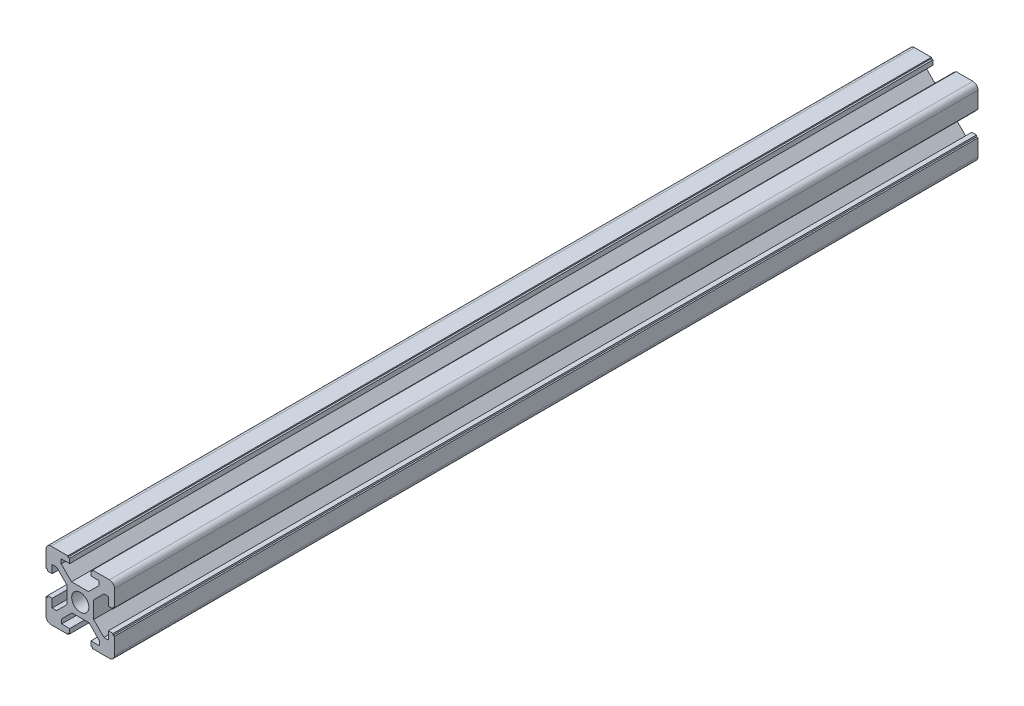
SolidWorks part; units mm, degrees
ref_plane "Front Plane" through (0, 0, 0) normal (0, 0, 1) x (1, 0, 0)
ref_plane "Top Plane" through (0, 0, 0) normal (0, 1, 0) x (1, 0, 0)
ref_plane "Right Plane" through (0, 0, 0) normal (1, 0, 0) x (0, 0, -1)
ref_plane "Plane1" through (0, 0, 0) normal (0, 0, -1) x (-1, 0, 0)
sketch "Sketch1" plane through (0, 0, 0) normal (0, 0, -1) x (-1, 0, 0)
  line L0 (-31.2291, 24.3895) -> (-31.2291, 19.5741)
  line L1 (-31.2291, 19.5741) -> (-30.8015, 19.5741)
  line L2 (-30.8015, 19.5741) -> (-30.8015, 19.0554)
  line L3 (-30.8015, 19.0554) -> (-29.4291, 19.0554)
  line L4 (-29.4291, 19.0554) -> (-29.4291, 21.5235)
  line L5 (-29.4291, 21.5235) -> (-28.1416, 21.5235)
  line L6 (-28.1416, 21.5235) -> (-25.1291, 18.511)
  line L7 (-25.1291, 18.511) -> (-25.1291, 13.533)
  line L8 (-25.1291, 13.533) -> (-28.1416, 10.5205)
  line L9 (-28.1416, 10.5205) -> (-29.4291, 10.5205)
  line L10 (-29.4291, 10.5205) -> (-29.4291, 12.8554)
  line L11 (-29.4291, 12.8554) -> (-30.8015, 12.8554)
  line L12 (-30.8015, 12.8554) -> (-30.8015, 12.3507)
  line L13 (-30.8015, 12.3507) -> (-31.2291, 12.3507)
  line L14 (-31.2291, 12.3507) -> (-31.2291, 7.5212)
  line L15 (-29.7291, 6.0212) -> (-24.8478, 6.0212)
  line L16 (-24.8478, 6.0212) -> (-24.8478, 6.383)
  line L17 (-24.8478, 6.383) -> (-24.3291, 6.383)
  line L18 (-24.3291, 6.383) -> (-24.3291, 7.7554)
  line L19 (-24.3291, 7.7554) -> (-26.7973, 7.7554)
  line L20 (-26.7973, 7.7554) -> (-26.7973, 9.0429)
  line L21 (-26.7973, 9.0429) -> (-23.7848, 12.0554)
  line L22 (-23.7848, 12.0554) -> (-18.8067, 12.0554)
  line L23 (-18.8067, 12.0554) -> (-15.7942, 9.0429)
  line L24 (-15.7942, 9.0429) -> (-15.7942, 7.7554)
  line L25 (-15.7942, 7.7554) -> (-18.1291, 7.7554)
  line L26 (-18.1291, 7.7554) -> (-18.1291, 6.383)
  line L27 (-18.1291, 6.383) -> (-17.6244, 6.383)
  line L28 (-17.6244, 6.383) -> (-17.6244, 6.0212)
  line L29 (-17.6244, 6.0212) -> (-12.7291, 6.0212)
  line L30 (-11.2291, 7.5212) -> (-11.2291, 12.3367)
  line L31 (-11.2291, 12.3367) -> (-11.6567, 12.3367)
  line L32 (-11.6567, 12.3367) -> (-11.6567, 12.8554)
  line L33 (-11.6567, 12.8554) -> (-13.0291, 12.8554)
  line L34 (-13.0291, 12.8554) -> (-13.0291, 10.3872)
  line L35 (-13.0291, 10.3872) -> (-14.3166, 10.3872)
  line L36 (-14.3166, 10.3872) -> (-17.3291, 13.3997)
  line L37 (-17.3291, 13.3997) -> (-17.3291, 18.3778)
  line L38 (-17.3291, 18.3778) -> (-14.3166, 21.3903)
  line L39 (-14.3166, 21.3903) -> (-13.0291, 21.3903)
  line L40 (-13.0291, 21.3903) -> (-13.0291, 19.0554)
  line L41 (-13.0291, 19.0554) -> (-11.6567, 19.0554)
  line L42 (-11.6567, 19.0554) -> (-11.6567, 19.56)
  line L43 (-11.6567, 19.56) -> (-11.2291, 19.56)
  line L44 (-11.2291, 19.56) -> (-11.2291, 24.3895)
  line L45 (-12.7291, 25.8895) -> (-17.6104, 25.8895)
  line L46 (-17.6104, 25.8895) -> (-17.6104, 25.5277)
  line L47 (-17.6104, 25.5277) -> (-18.1291, 25.5277)
  line L48 (-18.1291, 25.5277) -> (-18.1291, 24.1554)
  line L49 (-18.1291, 24.1554) -> (-15.661, 24.1554)
  line L50 (-15.661, 24.1554) -> (-15.661, 22.8679)
  line L51 (-15.661, 22.8679) -> (-18.6734, 19.8554)
  line L52 (-18.6734, 19.8554) -> (-23.6515, 19.8554)
  line L53 (-23.6515, 19.8554) -> (-26.664, 22.8679)
  line L54 (-26.664, 22.8679) -> (-26.664, 24.1554)
  line L55 (-26.664, 24.1554) -> (-24.3291, 24.1554)
  line L56 (-24.3291, 24.1554) -> (-24.3291, 25.5277)
  line L57 (-24.3291, 25.5277) -> (-24.8338, 25.5277)
  line L58 (-24.8338, 25.5277) -> (-24.8338, 25.8895)
  line L59 (-24.8338, 25.8895) -> (-29.7291, 25.8895)
  circle A0 centre (-21.2291, 15.9554) radius 2.5
  arc A1 (-31.2291, 7.5212) -> (-29.7291, 6.0212) centre (-29.7291, 7.5212) ccw
  arc A2 (-12.7291, 6.0212) -> (-11.2291, 7.5212) centre (-12.7291, 7.5212) ccw
  arc A3 (-11.2291, 24.3895) -> (-12.7291, 25.8895) centre (-12.7291, 24.3895) ccw
  arc A4 (-29.7291, 25.8895) -> (-31.2291, 24.3895) centre (-29.7291, 24.3895) ccw
extrude "Boss-Extrude1" add sketch "Sketch1" against normal blind 252
